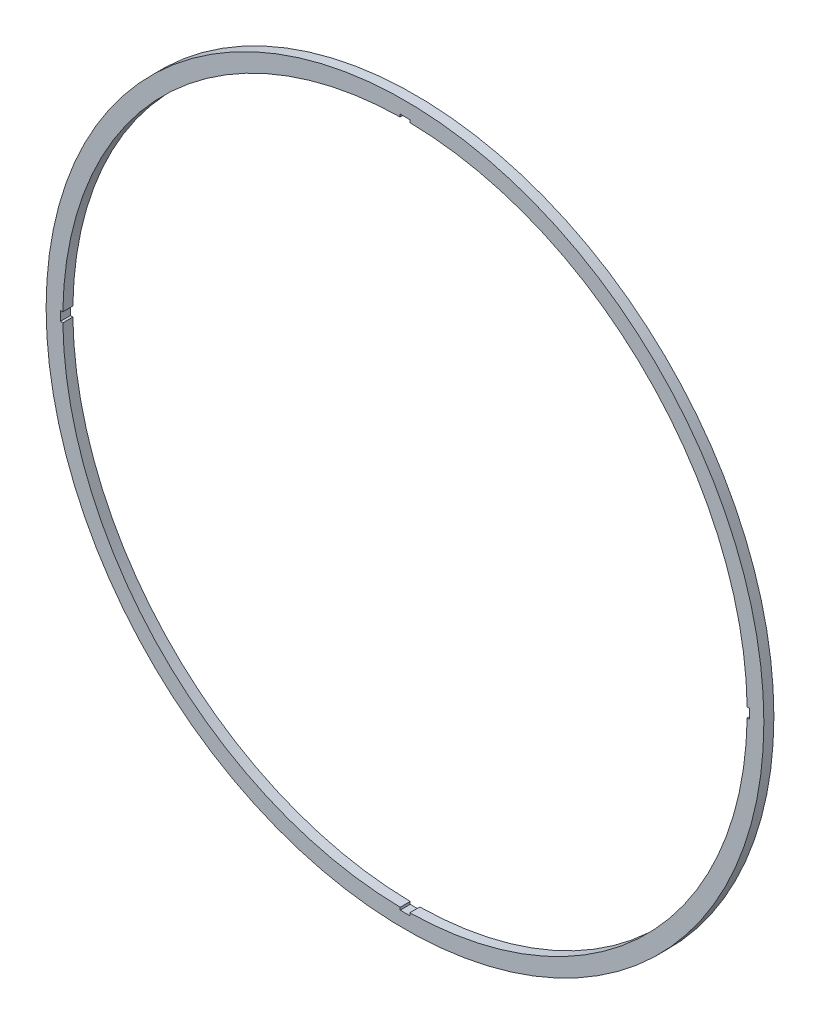
SolidWorks part; units mm, degrees
ref_plane "Front Plane" through (0, 0, 0) normal (0, 0, 1) x (1, 0, 0)
ref_plane "Top Plane" through (0, 0, 0) normal (0, 1, 0) x (1, 0, 0)
ref_plane "Right Plane" through (0, 0, 0) normal (1, 0, 0) x (0, 0, -1)
sketch "Sketch1" plane through (0, 0, 0) normal (0, 0, 1) x (1, 0, 0)
  line L0 (0, 0) -> (0, 484.7894) construction
  line L1 (413.0019, 5.7209) -> (409.9601, 5.7209)
  line L2 (-5.7209, 413.0019) -> (5.7209, 413.0019)
  line L3 (-5.7209, 413.0019) -> (-5.7209, 409.9601)
  line L5 (5.7209, 413.0019) -> (5.7209, 409.9601)
  line L6 (-5.7209, 413.0019) -> (0, 410) construction
  line L7 (0, 410) -> (5.7209, 413.0019) construction
  line L8 (413.0019, 5.7209) -> (413.0019, -5.7209)
  line L9 (413.0019, -5.7209) -> (409.9601, -5.7209)
  line L10 (5.7209, -413.0019) -> (5.7209, -409.9601)
  line L11 (5.7209, -413.0019) -> (-5.7209, -413.0019)
  line L12 (-5.7209, -413.0019) -> (-5.7209, -409.9601)
  line L13 (-413.0019, -5.7209) -> (-409.9601, -5.7209)
  line L14 (-413.0019, -5.7209) -> (-413.0019, 5.7209)
  line L15 (-413.0019, 5.7209) -> (-409.9601, 5.7209)
  circle A0 centre (0, 0) radius 430
  arc A1 (-5.7209, 409.9601) -> (-409.9601, 5.7209) centre (0, 0) ccw
  arc A2 (409.9601, 5.7209) -> (5.7209, 409.9601) centre (0, 0) ccw
  circle A3 centre (0, 0) radius 410 construction
  arc A4 (5.7209, -409.9601) -> (409.9601, -5.7209) centre (0, 0) ccw
  arc A5 (-409.9601, -5.7209) -> (-5.7209, -409.9601) centre (0, 0) ccw
  point P5 (0, 410)
  point P7 (430, 0)
  dimension "D1" = 20
  dimension "860" = 860
  dimension "D2" = 4
extrude "Boss-Extrude1" add sketch "Sketch1" along normal blind 12
